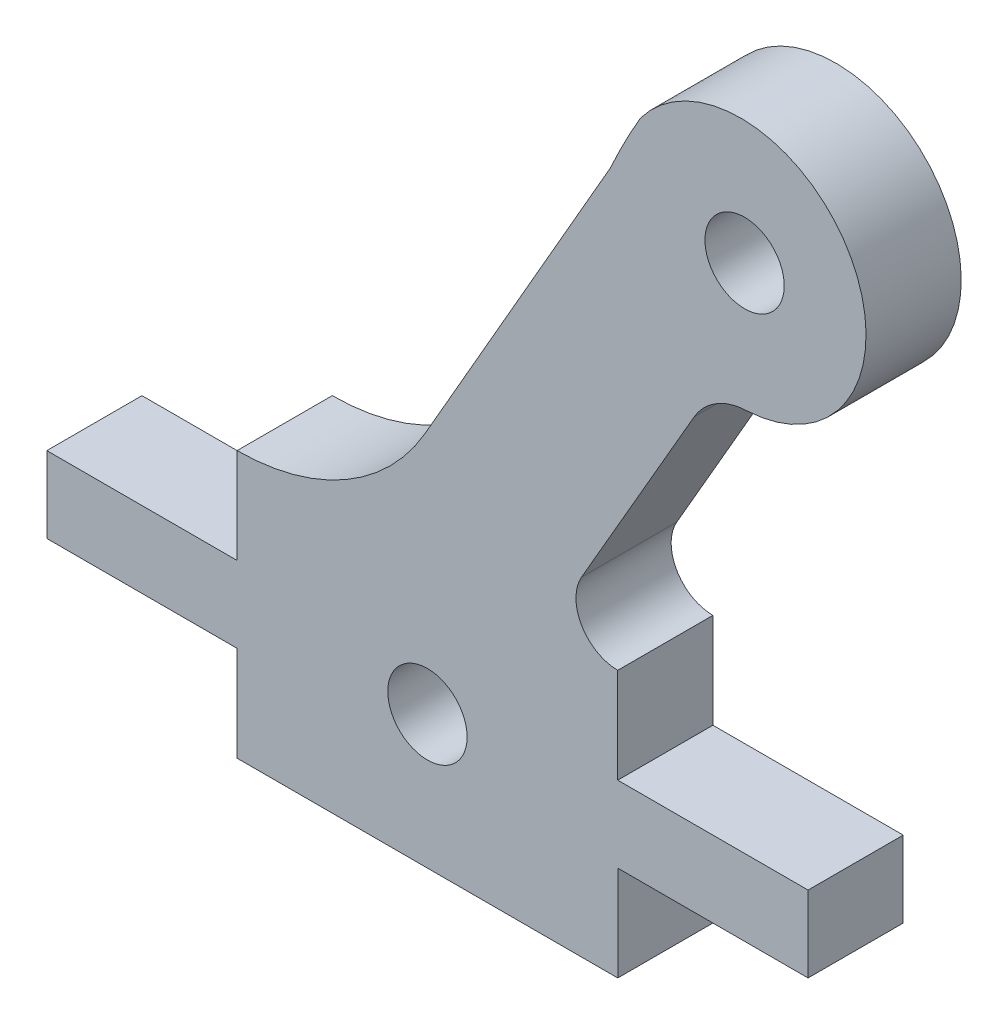
SolidWorks part; units mm, degrees
ref_plane "前基準面" through (0, 0, 0) normal (0, 0, 1) x (1, 0, 0)
ref_plane "上基準面" through (0, 0, 0) normal (0, 1, 0) x (1, 0, 0)
ref_plane "右基準面" through (0, 0, 0) normal (1, 0, 0) x (0, 0, -1)
sketch "草圖1" plane through (0, 0, 0) normal (0, 0, 1) x (1, 0, 0)
  line L0 (176.9978, 94.0906) -> (182.9978, 94.0906) construction
  line L1 (182.9978, 94.0906) -> (182.9978, 91.0906) construction
  line L2 (182.9978, 91.0906) -> (194.9978, 91.0906) construction
  line L3 (194.9978, 91.0906) -> (194.9978, 94.0906) construction
  line L4 (194.9978, 94.0906) -> (200.9975, 94.0906) construction
  line L5 (200.9974, 96.492) -> (194.9973, 96.4915) construction
  line L6 (194.9973, 96.4915) -> (194.9971, 99.4916) construction
  line L7 (193.8567, 101.4664) -> (197.4053, 107.6139) construction
  line L8 (194.7644, 113.0908) -> (188.9159, 102.9084) construction
  line L9 (182.9971, 99.4906) -> (182.9974, 96.4905) construction
  line L10 (182.9974, 96.4905) -> (176.9973, 96.49) construction
  line L11 (176.9978, 94.0906) -> (182.9978, 94.0906)
  line L12 (182.9978, 94.0906) -> (182.9978, 91.0906)
  line L13 (182.9978, 91.0906) -> (194.9978, 91.0906)
  line L14 (194.9978, 91.0906) -> (194.9978, 94.0906)
  line L15 (194.9978, 94.0906) -> (200.9975, 94.0906)
  line L16 (200.9974, 96.492) -> (194.9973, 96.4915)
  line L17 (194.9973, 96.4915) -> (194.9971, 99.4916)
  line L18 (193.8567, 101.4664) -> (197.4053, 107.6139)
  line L19 (194.7644, 113.0908) -> (188.9159, 102.9084)
  line L20 (182.9971, 99.4906) -> (182.9974, 96.4905)
  line L21 (182.9974, 96.4905) -> (176.9973, 96.49)
  line L22 (176.9973, 96.49) -> (176.9978, 94.0906)
  line L23 (200.9974, 96.492) -> (200.9975, 94.0906)
  circle A0 centre (188.9974, 95.2911) radius 1.25 construction
  arc A1 (193.8567, 101.4664) -> (194.9971, 99.4916) centre (194.9969, 100.8081) ccw construction
  arc A2 (199.0903, 108.6134) -> (197.4053, 107.6139) centre (199.1374, 106.6139) ccw construction
  circle A3 centre (198.996, 112.6123) radius 1.25 construction
  arc A4 (199.0903, 108.6134) -> (195.7151, 114.9302) centre (198.8749, 112.5585) ccw construction
  arc A5 (195.7151, 114.9302) -> (194.7644, 113.0908) centre (213.1273, 104.7653) ccw construction
  arc A6 (182.9971, 99.4906) -> (188.9159, 102.9084) centre (182.9967, 106.3252) ccw construction
  circle A7 centre (188.9974, 95.2911) radius 1.25
  arc A8 (193.8567, 101.4664) -> (194.9971, 99.4916) centre (194.9969, 100.8081) ccw
  arc A9 (199.0903, 108.6134) -> (197.4053, 107.6139) centre (199.1374, 106.6139) ccw
  circle A10 centre (198.996, 112.6123) radius 1.25
  arc A11 (199.0903, 108.6134) -> (195.7151, 114.9302) centre (198.8749, 112.5585) ccw
  arc A12 (195.7151, 114.9302) -> (194.7644, 113.0908) centre (213.1273, 104.7653) ccw
  arc A13 (182.9971, 99.4906) -> (188.9159, 102.9084) centre (182.9967, 106.3252) ccw
extrude "填料-伸長1" add sketch "草圖1" along normal blind 3
